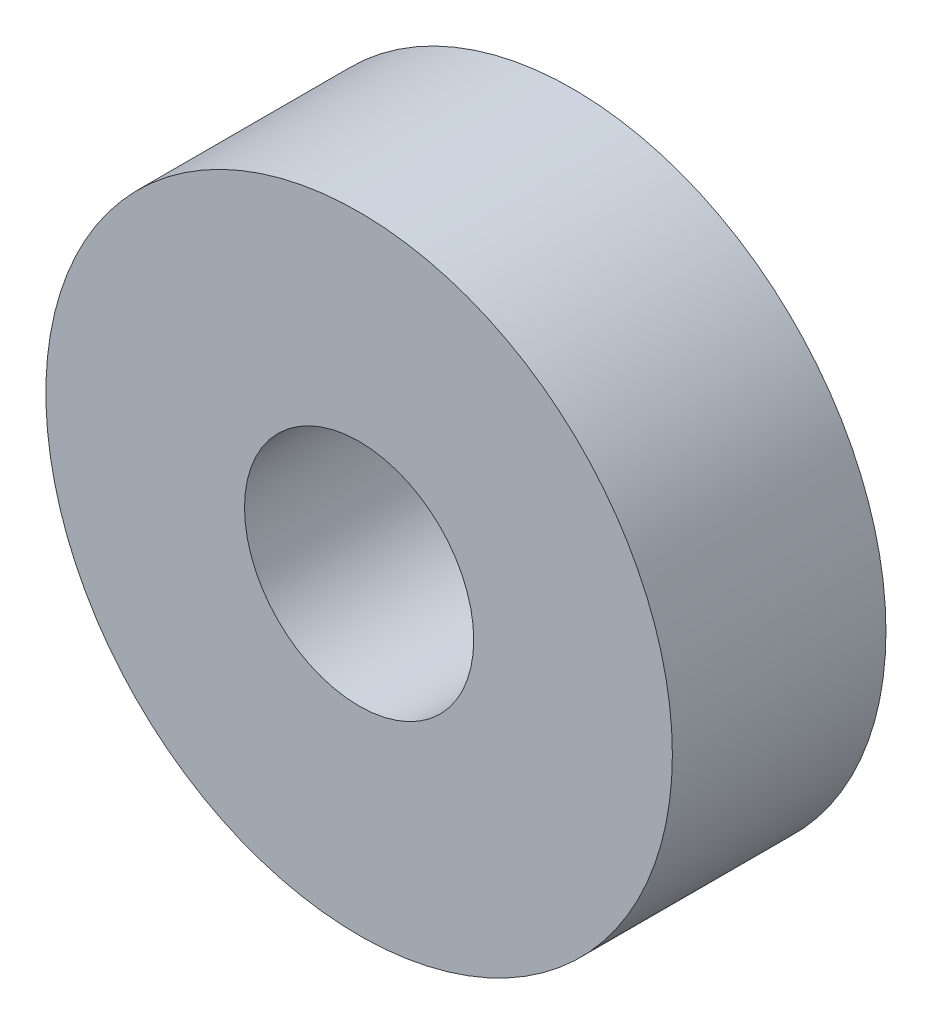
SolidWorks part; units mm, degrees
ref_plane "Front Plane" through (0, 0, 0) normal (0, 0, 1) x (1, 0, 0)
ref_plane "Top Plane" through (0, 0, 0) normal (0, 1, 0) x (1, 0, 0)
ref_plane "Right Plane" through (0, 0, 0) normal (1, 0, 0) x (0, 0, -1)
sketch "Sketch1" plane through (0, 0, 0) normal (0, 0, 1) x (1, 0, 0)
  circle A0 centre (0, 0) radius 22
  dimension "D1" = 44
extrude "Boss-Extrude1" add sketch "Sketch1" along normal blind 15
sketch "Sketch2" plane through (0, 0, 0) normal (0, 0, -1) x (-1, 0, 0)
  circle A0 centre (0, 0) radius 17.85
  circle A1 centre (0, 0) radius 12.5
  dimension "D1" = 35.7
  dimension "D2" = 25
extrude "Cut-Extrude1" cut sketch "Sketch2" against normal blind 10
sketch "Sketch3" plane through (0, 0, 15) normal (0, 0, 1) x (1, 0, 0)
  circle A0 centre (0, 0) radius 8.05
  dimension "D1" = 16.1
extrude "Cut-Extrude2" cut sketch "Sketch3" against normal through all
